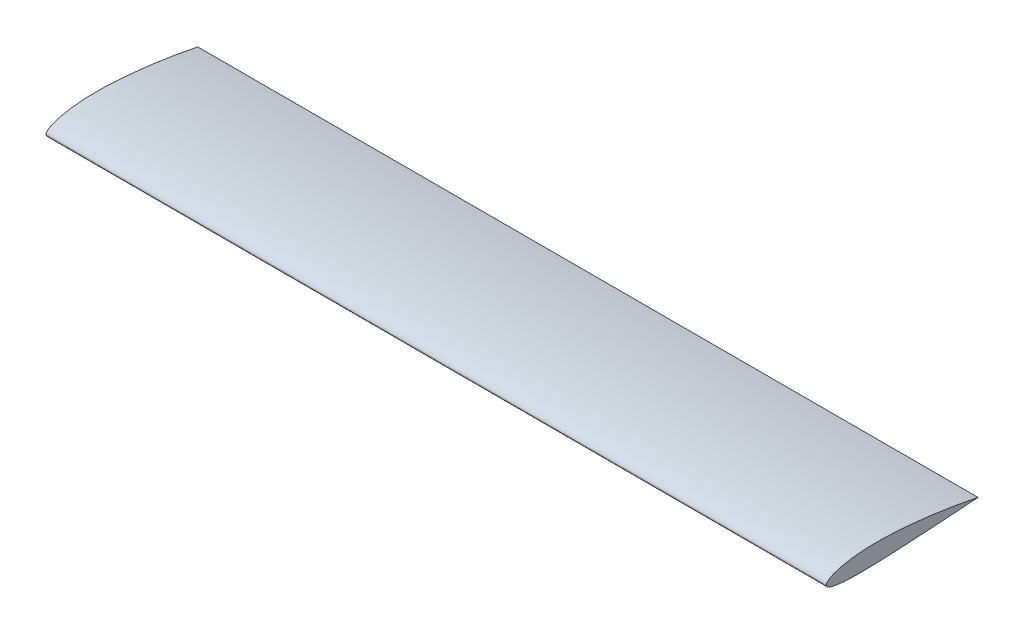
SolidWorks part; units mm, degrees
ref_plane "Front Plane" through (0, 0, 0) normal (0, 0, 1) x (1, 0, 0)
ref_plane "Top Plane" through (0, 0, 0) normal (0, 1, 0) x (1, 0, 0)
ref_plane "Right Plane" through (0, 0, 0) normal (1, 0, 0) x (0, 0, -1)
curve "Curve1"
  spline degree 3 poles (0, 25.4, 0.0064) (0, 25.2657, 0.0346) (0, 24.9974, 0.0911) (0, 24.5944, 0.1721) (0, 24.1917, 0.2509) (0, 23.7893, 0.3278) (0, 23.3874, 0.4029) (0, 22.9859, 0.4765) (0, 22.5851, 0.5485) (0, 22.1849, 0.619) (0, 21.7856, 0.688) (0, 21.3872, 0.7554) (0, 20.9898, 0.8212) (0, 20.5935, 0.8853) (0, 20.1985, 0.9476) (0, 19.8047, 1.0082) (0, 19.4123, 1.067) (0, 19.0215, 1.124) (0, 18.6322, 1.1792) (0, 18.2447, 1.2326) (0, 17.859, 1.2841) (0, 17.4751, 1.3339) (0, 17.0933, 1.382) (0, 16.7135, 1.4283) (0, 16.3359, 1.4729) (0, 15.9606, 1.5158) (0, 15.5877, 1.5571) (0, 15.2173, 1.5967) (0, 14.8494, 1.6346) (0, 14.4842, 1.6709) (0, 14.1217, 1.7054) (0, 13.7621, 1.7383) (0, 13.4054, 1.7695) (0, 13.0517, 1.7989) (0, 12.7011, 1.8265) (0, 12.3537, 1.8522) (0, 12.0097, 1.8761) (0, 11.6689, 1.8981) (0, 11.3317, 1.918) (0, 10.9979, 1.936) (0, 10.6678, 1.9519) (0, 10.3414, 1.9657) (0, 10.0188, 1.9774) (0, 9.7001, 1.9869) (0, 9.3853, 1.9942) (0, 9.0746, 1.9993) (0, 8.7679, 2.0022) (0, 8.4655, 2.0029) (0, 8.1673, 2.0014) (0, 7.8734, 1.9977) (0, 7.584, 1.9918) (0, 7.2991, 1.9837) (0, 7.0187, 1.9735) (0, 6.7429, 1.9612) (0, 6.4718, 1.9468) (0, 6.2055, 1.9304) (0, 5.944, 1.912) (0, 5.6874, 1.8917) (0, 5.4358, 1.8694) (0, 5.1892, 1.8454) (0, 4.9477, 1.8195) (0, 4.7114, 1.792) (0, 4.4802, 1.7628) (0, 4.2543, 1.7319) (0, 4.0338, 1.6995) (0, 3.8186, 1.6656) (0, 3.6089, 1.6303) (0, 3.4046, 1.5936) (0, 3.2059, 1.5556) (0, 3.0127, 1.5163) (0, 2.8252, 1.4759) (0, 2.6434, 1.4343) (0, 2.4673, 1.3917) (0, 2.297, 1.3481) (0, 2.1325, 1.3035) (0, 1.9738, 1.2581) (0, 1.8211, 1.2119) (0, 1.6742, 1.1649) (0, 1.5334, 1.1173) (0, 1.3985, 1.0691) (0, 1.2697, 1.0204) (0, 1.147, 0.9712) (0, 1.0304, 0.9215) (0, 0.9199, 0.8715) (0, 0.8155, 0.8212) (0, 0.7173, 0.7706) (0, 0.6254, 0.7198) (0, 0.5396, 0.6689) (0, 0.4601, 0.6178) (0, 0.3869, 0.5666) (0, 0.3199, 0.5153) (0, 0.2592, 0.4639) (0, 0.2049, 0.4126) (0, 0.1568, 0.3611) (0, 0.1151, 0.3097) (0, 0.0797, 0.2582) (0, 0.0507, 0.2067) (0, 0.0281, 0.1551) (0, 0.0119, 0.1034) (0, 0.0022, 0.0517) (0, -0.0011, 0.0014) (0, 0.0021, -0.0476) (0, 0.0119, -0.095) (0, 0.0281, -0.1421) (0, 0.0507, -0.1886) (0, 0.0797, -0.2345) (0, 0.1151, -0.2796) (0, 0.1568, -0.3238) (0, 0.2049, -0.3671) (0, 0.2593, -0.4092) (0, 0.32, -0.4502) (0, 0.387, -0.49) (0, 0.4602, -0.5285) (0, 0.5397, -0.5656) (0, 0.6255, -0.6013) (0, 0.7175, -0.6357) (0, 0.8157, -0.6686) (0, 0.92, -0.7001) (0, 1.0306, -0.7301) (0, 1.1472, -0.7588) (0, 1.2699, -0.786) (0, 1.3988, -0.8119) (0, 1.5336, -0.8364) (0, 1.6745, -0.8596) (0, 1.8213, -0.8815) (0, 1.974, -0.9021) (0, 2.1327, -0.9215) (0, 2.2972, -0.9397) (0, 2.4675, -0.9567) (0, 2.6436, -0.9725) (0, 2.8254, -0.9871) (0, 3.0129, -1.0006) (0, 3.206, -1.0129) (0, 3.4048, -1.0241) (0, 3.609, -1.0341) (0, 3.8188, -1.043) (0, 4.0339, -1.0507) (0, 4.2545, -1.0573) (0, 4.4804, -1.0628) (0, 4.7115, -1.0671) (0, 4.9478, -1.0703) (0, 5.1893, -1.0723) (0, 5.4359, -1.0732) (0, 5.6875, -1.073) (0, 5.9441, -1.0718) (0, 6.2056, -1.0694) (0, 6.4719, -1.0661) (0, 6.7429, -1.0617) (0, 7.0187, -1.0564) (0, 7.2991, -1.0502) (0, 7.584, -1.0431) (0, 7.8735, -1.0352) (0, 8.1673, -1.0265) (0, 8.4655, -1.017) (0, 8.7679, -1.0069) (0, 9.0746, -0.996) (0, 9.3853, -0.9846) (0, 9.7001, -0.9725) (0, 10.0188, -0.9599) (0, 10.3414, -0.9466) (0, 10.6678, -0.9328) (0, 10.9979, -0.9185) (0, 11.3316, -0.9035) (0, 11.6689, -0.888) (0, 12.0096, -0.8718) (0, 12.3537, -0.855) (0, 12.7011, -0.8375) (0, 13.0517, -0.8194) (0, 13.4053, -0.8005) (0, 13.762, -0.781) (0, 14.1217, -0.7608) (0, 14.4841, -0.7398) (0, 14.8494, -0.7181) (0, 15.2172, -0.6958) (0, 15.5877, -0.6729) (0, 15.9606, -0.6493) (0, 16.3359, -0.6253) (0, 16.7134, -0.6007) (0, 17.0932, -0.5758) (0, 17.475, -0.5506) (0, 17.8589, -0.5252) (0, 18.2446, -0.4996) (0, 18.6321, -0.4739) (0, 19.0214, -0.4481) (0, 19.4122, -0.4224) (0, 19.8046, -0.3966) (0, 20.1983, -0.3708) (0, 20.5934, -0.3449) (0, 20.9897, -0.3189) (0, 21.3871, -0.2926) (0, 21.7855, -0.2659) (0, 22.1848, -0.2386) (0, 22.585, -0.2108) (0, 22.9858, -0.1822) (0, 23.3872, -0.153) (0, 23.7892, -0.1231) (0, 24.1915, -0.0928) (0, 24.5941, -0.0626) (0, 24.997, -0.0331) (0, 25.2657, -0.0153) (0, 25.4, -0.0064) knots 0 0 0 0 0.007941 0.015868 0.023782 0.031684 0.039571 0.047444 0.055299 0.063136 0.070953 0.078747 0.086517 0.09426 0.101975 0.10966 0.117312 0.124931 0.132515 0.14006 0.147567 0.155033 0.162457 0.169836 0.17717 0.184456 0.191693 0.198879 0.206013 0.213092 0.220115 0.227081 0.233988 0.240834 0.247617 0.254336 0.260989 0.267575 0.274092 0.280538 0.286913 0.293214 0.299441 0.305592 0.311665 0.31766 0.323575 0.329409 0.33516 0.340829 0.346413 0.351912 0.357324 0.362648 0.367884 0.373031 0.378086 0.383051 0.387923 0.392702 0.397387 0.401977 0.406471 0.410868 0.415168 0.41937 0.423472 0.427475 0.431378 0.435179 0.438879 0.442477 0.445971 0.449362 0.45265 0.455833 0.458911 0.461884 0.464751 0.467513 0.470169 0.47272 0.475165 0.477504 0.479738 0.481867 0.483893 0.485816 0.487638 0.48936 0.490986 0.492517 0.493957 0.495311 0.496586 0.497786 0.498922 0.500002 0.50104 0.502047 0.503039 0.503952 0.504878 0.505831 0.506824 0.507866 0.508967 0.510136 0.51138 0.512704 0.514115 0.515615 0.517209 0.518901 0.520691 0.522584 0.524581 0.526682 0.528891 0.531207 0.533632 0.536166 0.538809 0.541562 0.544425 0.547398 0.550481 0.553673 0.556974 0.560384 0.563903 0.567529 0.571261 0.5751 0.579045 0.583094 0.587247 0.591503 0.595862 0.600321 0.60488 0.609539 0.614295 0.619148 0.624097 0.629141 0.634278 0.639507 0.644828 0.650237 0.655735 0.66132 0.666991 0.672745 0.678583 0.684501 0.690499 0.696575 0.702728 0.708956 0.715257 0.72163 0.728074 0.734587 0.741166 0.747811 0.75452 0.761292 0.768124 0.775014 0.781962 0.788966 0.796023 0.803132 0.810291 0.817498 0.824752 0.832051 0.839391 0.846773 0.854193 0.86165 0.869142 0.876666 0.884222 0.891806 0.899418 0.907055 0.914715 0.922398 0.9301 0.93782 0.945557 0.953308 0.961072 0.968847 0.97663 0.984418 0.99221 1 1 1 1
sketch "Sketch1" plane through (0, 0, 0) normal (1, 0, 0) x (0, 0, -1)
  line L0 (0, -34.2555) -> (0, 34.2555) construction
  line L1 (0, 0) -> (355.7016, 0) construction
  line L2 (355.7016, -0.0889) -> (355.7016, 0.0889)
  spline S1 degree 3 poles (355.7016, 0.0889) (353.821, 0.4846) (350.0629, 1.2754) (344.4197, 2.409) (338.7804, 3.5132) (333.1454, 4.5891) (327.5162, 5.641) (321.8943, 6.6708) (314.4189, 8.0137) (303.257, 9.9613) (290.2772, 12.1108) (277.369, 14.1228) (266.4033, 15.7436) (251.9793, 17.7585) (237.6887, 19.5838) (223.5484, 21.2273) (213.1408, 22.3588) (202.8769, 23.3975) (192.7669, 24.3422) (182.821, 25.1904) (173.0491, 25.938) (161.9218, 26.6836) (149.5344, 27.3539) (135.9897, 27.8484) (122.942, 28.0679) (110.4211, 28.0086) (99.7007, 27.7089) (90.6939, 27.2701) (83.3038, 26.7835) (76.1879, 26.1886) (69.3535, 25.4909) (62.8074, 24.6967) (56.5561, 23.8124) (50.6059, 22.8444) (44.9628, 21.7997) (39.6324, 20.6852) (35.3947, 19.6899) (31.4198, 18.6717) (28.4021, 17.8332) (25.5014, 16.9556) (23.4454, 16.2981) (21.4729, 15.6314) (19.5845, 14.9562) (17.7807, 14.2734) (16.062, 13.584) (14.4286, 12.8887) (12.881, 12.1883) (11.4197, 11.4836) (10.0449, 10.7752) (8.757, 10.0639) (7.5563, 9.3501) (6.443, 8.6344) (5.4173, 7.9173) (4.4796, 7.1992) (3.63, 6.4802) (2.8687, 5.7606) (2.1958, 5.0406) (1.6116, 4.3201) (1.1162, 3.599) (0.71, 2.8773) (0.3934, 2.1549) (0.1666, 1.4316) (0.0307, 0.7075) (-0.0151, 0.0023) (0.0301, -0.6834) (0.1668, -1.3473) (0.3934, -2.0063) (0.7102, -2.6581) (1.1165, -3.3007) (1.612, -3.9325) (2.1965, -4.5518) (2.8697, -5.1573) (3.6313, -5.7477) (4.4813, -6.3218) (5.4193, -6.8786) (6.4453, -7.4172) (7.5589, -7.9371) (8.76, -8.4376) (10.0481, -8.9184) (11.4232, -9.3792) (12.8847, -9.8201) (14.4325, -10.241) (16.066, -10.642) (17.7849, -11.0235) (19.5888, -11.3858) (21.4773, -11.729) (23.4498, -12.0538) (25.5059, -12.3603) (27.6451, -12.6492) (29.8668, -12.9206) (32.1705, -13.1749) (35.403, -13.4968) (39.6448, -13.8551) (44.9745, -14.214) (50.6169, -14.509) (56.5663, -14.7403) (62.8168, -14.9075) (69.3622, -15.0107) (76.1958, -15.0506) (83.3108, -15.0286) (90.6999, -14.9474) (98.3559, -14.8106) (106.2708, -14.6225) (114.4369, -14.3883) (122.846, -14.1126) (131.4894, -13.7998) (140.3587, -13.4531) (149.4448, -13.0741) (161.9675, -12.5201) (174.7476, -11.9046) (187.7718, -11.2203) (197.8008, -10.6626) (207.9888, -10.0652) (220.0884, -9.3219) (232.3456, -8.533) (244.7486, -7.7149) (255.5228, -6.9989) (264.5664, -6.3993) (273.6873, -5.7979) (282.8763, -5.1951) (293.956, -4.4688) (303.2297, -3.852) (310.6767, -3.3441) (316.28, -2.9539) (321.8933, -2.5538) (327.515, -2.1436) (333.1438, -1.7248) (338.778, -1.3003) (344.4165, -0.8778) (350.0574, -0.4634) (353.8203, -0.2137) (355.7016, -0.0889) knots 0 0 0 0 0.007941 0.015868 0.023782 0.031684 0.039571 0.047444 0.055299 0.070953 0.09426 0.10966 0.124931 0.14006 0.169836 0.184456 0.198879 0.213092 0.227081 0.240834 0.254336 0.267575 0.286913 0.305592 0.323575 0.340829 0.357324 0.367884 0.378086 0.387923 0.397387 0.406471 0.415168 0.423472 0.431378 0.438879 0.445971 0.449362 0.455833 0.458911 0.461884 0.464751 0.467513 0.470169 0.47272 0.475165 0.477504 0.479738 0.481867 0.483893 0.485816 0.487638 0.48936 0.490986 0.492517 0.493957 0.495311 0.496586 0.497786 0.498922 0.500002 0.50104 0.502047 0.503039 0.503952 0.504878 0.505831 0.506824 0.507866 0.508967 0.510136 0.51138 0.512704 0.514115 0.515615 0.517209 0.518901 0.520691 0.522584 0.524581 0.526682 0.528891 0.531207 0.533632 0.536166 0.538809 0.541562 0.544425 0.547398 0.550481 0.553673 0.556974 0.563903 0.571261 0.579045 0.587247 0.595862 0.60488 0.614295 0.624097 0.634278 0.644828 0.655735 0.666991 0.678583 0.690499 0.702728 0.715257 0.728074 0.75452 0.768124 0.781962 0.796023 0.810291 0.832051 0.846773 0.86165 0.876666 0.884222 0.899418 0.914715 0.9301 0.93782 0.945557 0.953308 0.961072 0.968847 0.97663 0.984418 0.99221 1 1 1 1
  point P4 (0, 0)
  point P7 (0, 0)
  point P8 (355.7016, 0)
  point P9 (0, 0)
  dimension "D1" = 355.7016
extrude "Boss-Extrude1" add sketch "Sketch1" along normal mid plane 1828.8
